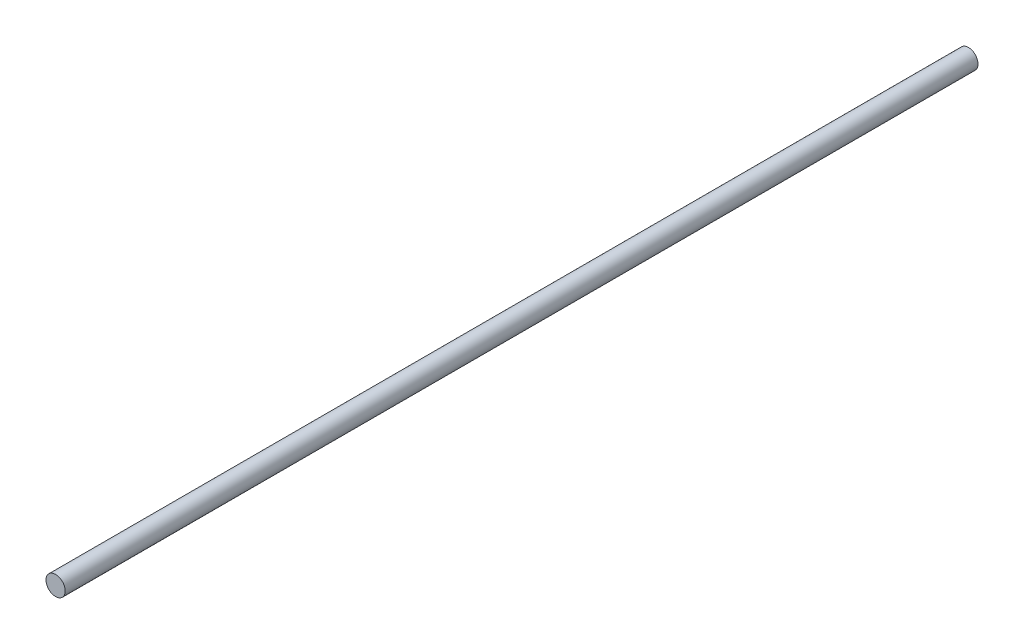
SolidWorks part; units mm, degrees
ref_plane "Alzado" through (0, 0, 0) normal (0, 0, 1) x (1, 0, 0)
ref_plane "Planta" through (0, 0, 0) normal (0, 1, 0) x (1, 0, 0)
ref_plane "Vista lateral" through (0, 0, 0) normal (1, 0, 0) x (0, 0, -1)
sketch "Croquis1" plane through (0, 0, 0) normal (0, 0, 1) x (1, 0, 0)
  circle A0 centre (0, 0) radius 10
  dimension "D1" = 20
extrude "Saliente-Extruir2" add sketch "Croquis1" along normal blind 950
sketch "Croquis2" plane through (0, 0, 0) normal (0, 1, 0) x (1, 0, 0)
  circle A1 centre (0, -465) radius 10
  circle A2 centre (0, -485) radius 10
  dimension "D1" = 20
  dimension "D2" = 465
  dimension "D3" = 20
